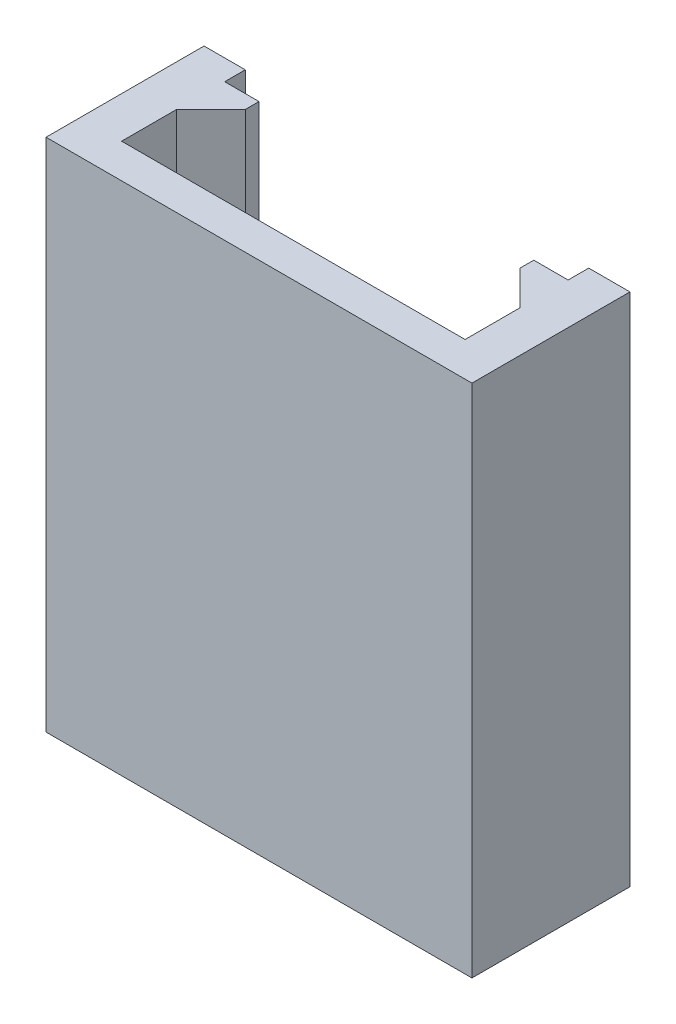
SolidWorks part; units mm, degrees
ref_plane "Přední rovina" through (0, 0, 0) normal (0, 0, 1) x (1, 0, 0)
ref_plane "Horní rovina" through (0, 0, 0) normal (0, 1, 0) x (1, 0, 0)
ref_plane "Pravá rovina" through (0, 0, 0) normal (1, 0, 0) x (0, 0, -1)
sketch "Skica1" plane through (0, 0, 0) normal (0, 1, 0) x (1, 0, 0)
  line L0 (-5, 0) -> (5, 0)
  line L1 (0, -1000) -> (0, 49000) construction
  line L2 (-5, 0) -> (-5, 1.6)
  line L3 (-5, 1.6) -> (-4, 2.6)
  line L4 (-4, 2.6) -> (-4, 3)
  line L6 (-6.2, 3.6) -> (-6.2, -1)
  line L7 (-6.2, -1) -> (6.2, -1)
  line L8 (0, -1) -> (0, 0) construction
  line L9 (-4, 3) -> (-5, 3)
  line L10 (-5, 3) -> (-5, 3.6)
  line L11 (-5, 3.6) -> (-6.2, 3.6)
  line L12 (5, 0) -> (5, 1.6)
  line L13 (5, 1.6) -> (4, 2.6)
  line L14 (4, 2.6) -> (4, 3)
  line L15 (4, 3) -> (5, 3)
  line L16 (5, 3) -> (5, 3.6)
  line L17 (6.2, 3.6) -> (6.2, -1)
  line L18 (5, 3.6) -> (6.2, 3.6)
  dimension "D2" = 0.4
  dimension "D1" = 5
  dimension "D3" = 1
  dimension "D4" = 1.2
  dimension "D5" = 1
  dimension "D6" = 1.6
  dimension "D7" = 1
  dimension "D8" = 0.6
extrude "Přidat vysunutím1" add sketch "Skica1" along normal blind 15
